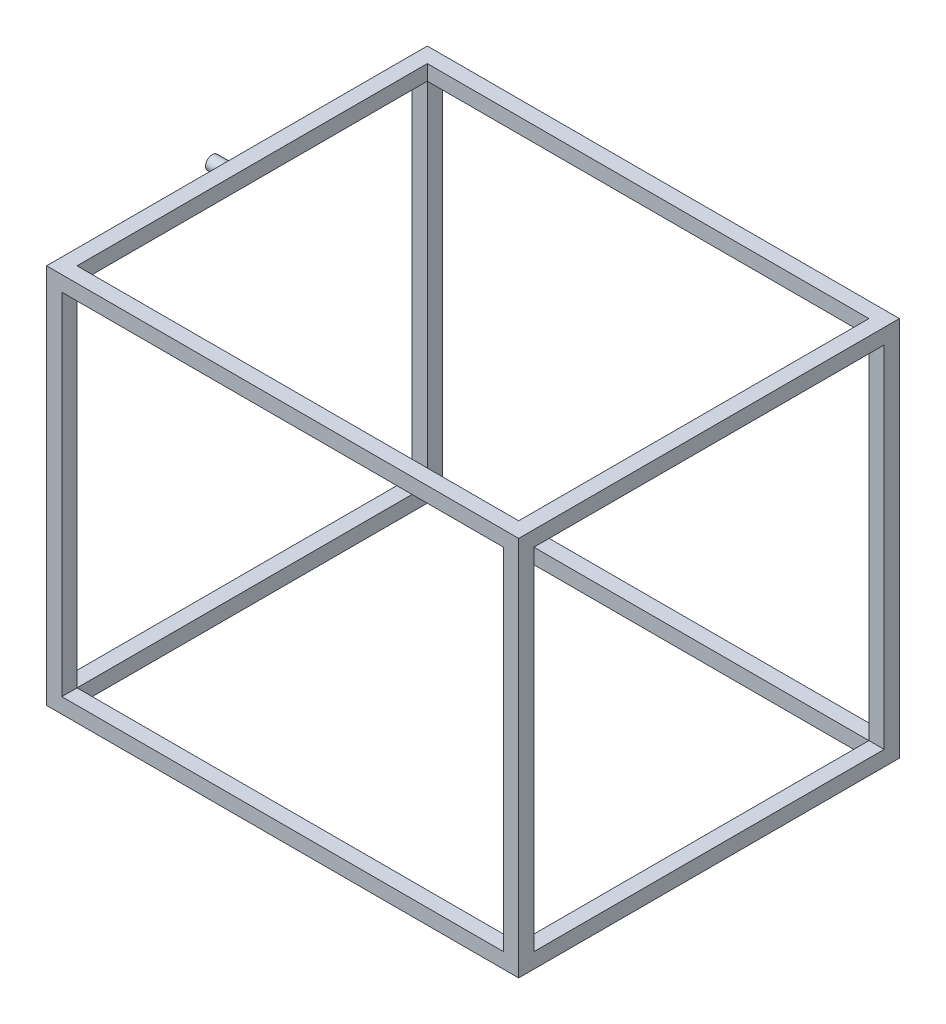
SolidWorks part; units mm, degrees
ref_plane "前视基准面" through (0, 0, 0) normal (0, 0, 1) x (1, 0, 0)
ref_plane "上视基准面" through (0, 0, 0) normal (0, 1, 0) x (1, 0, 0)
ref_plane "右视基准面" through (0, 0, 0) normal (1, 0, 0) x (0, 0, -1)
sketch "草图1" plane through (0, 0, 0) normal (0, 0, 1) x (1, 0, 0)
  line L1 (0, 0) -> (20, 0)
  line L2 (0, 0) -> (0, -20)
  line L3 (0, -20) -> (20, -20)
  line L4 (20, 0) -> (20, -20)
  dimension "D1" = 20
  dimension "D2" = 20
extrude "凸台-拉伸1" add sketch "草图1" along normal blind 500
sketch "草图2" plane through (0, 0, 0) normal (-1, 0, 0) x (0, 0, 1)
  line L0 (500, 0) -> (480, 0)
  line L1 (500, 0) -> (0, 0) construction
  line L2 (480, 0) -> (480, -20)
  line L3 (500, -20) -> (0, -20) construction
  line L4 (480, -20) -> (500, -20)
  line L5 (500, -20) -> (500, 0)
  line L6 (0, 0) -> (20, 0)
  line L7 (20, 0) -> (20, -20)
  line L8 (20, -20) -> (0, -20)
  line L9 (0, -20) -> (0, 0)
  dimension "D1" = 20
  dimension "D2" = 20
  dimension "D3" = 20
extrude "凸台-拉伸2" add sketch "草图2" along normal blind 580
sketch "草图3" plane through (-580, 0, 0) normal (-1, 0, 0) x (0, 0, 1)
  line L0 (0, 0) -> (500, 0)
  line L1 (500, 0) -> (500, -20)
  line L2 (500, -20) -> (0, -20)
  line L3 (0, -20) -> (0, 0)
extrude "凸台-拉伸3" add sketch "草图3" along normal blind 20
sketch "草图4" plane through (0, 0, 0) normal (0, 1, 0) x (1, 0, 0)
  line L0 (0, -20) -> (20, -20)
  line L1 (20, -500) -> (20, 0) construction
  line L2 (20, -20) -> (20, 0)
  line L3 (20, 0) -> (0, 0)
  line L4 (0, 0) -> (0, -20)
  line L5 (20, -500) -> (0, -500)
  line L6 (20, -500) -> (-600, -500) construction
  line L7 (0, -500) -> (0, -480)
  line L8 (0, -480) -> (20, -480)
  line L9 (20, -480) -> (20, -500)
  line L10 (-600, -500) -> (-600, -480)
  line L11 (-600, -500) -> (-600, 0) construction
  line L12 (-600, -480) -> (-580, -480)
  line L13 (-580, -480) -> (-580, -500)
  line L14 (-580, -500) -> (-600, -500)
  line L15 (-600, 0) -> (-600, -20)
  line L16 (-600, -20) -> (-580, -20)
  line L17 (-580, -20) -> (-580, 0)
  line L18 (20, 0) -> (-600, 0) construction
  line L19 (-580, 0) -> (-600, 0)
extrude "凸台-拉伸4" add sketch "草图4" along normal blind 460
sketch "草图5" plane through (0, 460, 0) normal (0, 1, 0) x (1, 0, 0)
  line L0 (0, -20) -> (0, -480)
  line L1 (0, -480) -> (-580, -480)
  line L2 (-580, -480) -> (-580, -20)
  line L3 (-580, -20) -> (0, -20)
  line L4 (-600, 0) -> (20, 0)
  line L5 (20, 0) -> (20, -500)
  line L6 (20, -500) -> (-600, -500)
  line L7 (-600, -500) -> (-600, 0)
  dimension "D1" = 20
extrude "凸台-拉伸5" add sketch "草图5" along normal blind 20
sketch "草图6" plane through (-600, 0, 0) normal (-1, 0, 0) x (0, 0, 1)
  circle A0 centre (262.3599, 468.8641) radius 8.8641
extrude "凸台-拉伸6" add sketch "草图6" along normal blind 20
